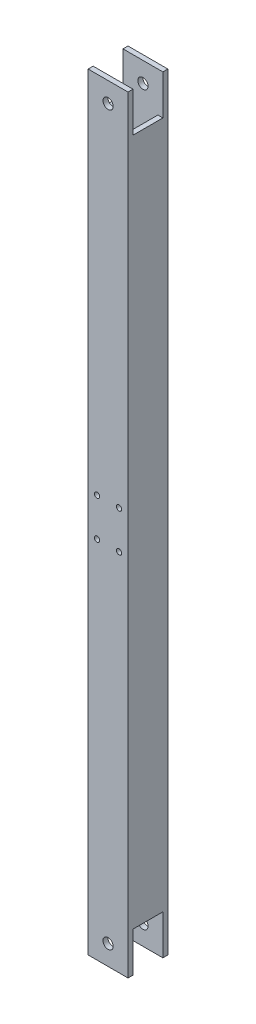
SolidWorks part; units mm, degrees
material "6061 Alloy"
ref_plane "Front Plane" through (0, 0, 0) normal (0, 0, 1) x (1, 0, 0)
ref_plane "Top Plane" through (0, 0, 0) normal (0, 1, 0) x (1, 0, 0)
ref_plane "Right Plane" through (0, 0, 0) normal (1, 0, 0) x (0, 0, -1)
sketch "Sketch1" plane through (0, 0, 0) normal (0, 1, 0) x (1, 0, 0)
  line L0 (3.175, -3.175) -> (22.225, -3.175)
  line L1 (0, 0) -> (25.4, 0)
  line L2 (0, 0) -> (0, -25.4)
  line L3 (0, -25.4) -> (25.4, -25.4)
  line L4 (25.4, 0) -> (25.4, -25.4)
  line L5 (22.225, -3.175) -> (22.225, -22.225)
  line L6 (3.175, -22.225) -> (22.225, -22.225)
  line L7 (3.175, -3.175) -> (3.175, -22.225)
  dimension "D1" = 25.4
  dimension "D2" = 25.4
  dimension "D3" = 3.175
extrude "Boss-Extrude1" add sketch "Sketch1" along normal blind 488.95
sketch "Sketch2" plane through (0, 0, 0) normal (0, 0, -1) x (-1, 0, 0)
  line L0 (-12.7, 488.95) -> (-12.7, 0)
  line L1 (-25.4, 488.95) -> (0, 488.95) construction
  line L2 (-25.4, 0) -> (0, 0) construction
  circle A0 centre (-12.7, 244.475) radius 14
  circle A1 centre (1.3, 244.475) radius 1.7
  circle A2 centre (-5.7, 232.3506) radius 1.7
  circle A3 centre (-19.7, 232.3506) radius 1.7
  circle A4 centre (-26.7, 244.475) radius 1.7
  circle A5 centre (-19.7, 256.5994) radius 1.7
  circle A6 centre (-5.7, 256.5994) radius 1.7
  point P23 (-12.7, 244.475)
  dimension "D1" = 28
  dimension "D2" = 3.4
  dimension "D3" = 6
extrude "Cut-Extrude1" cut sketch "Sketch2" against normal up to surface (25.4 mm away) contours A6 | A5 | A3 | A2 up to face at (12.7, 244.475, 25.4)
sketch "Sketch5" plane through (0, 0, 0) normal (-1, 0, 0) x (0, 0, 1)
  line L0 (3.175, 0) -> (22.225, 0)
  line L2 (3.175, 0) -> (3.175, 25.4006)
  line L3 (3.175, 25.4006) -> (22.225, 25.4006)
  line L4 (22.225, 25.4006) -> (22.225, 0)
  point P3 (12.7, 0)
extrude "Cut-Extrude2" cut sketch "Sketch5" against normal through all
ref_plane "Plane1" through (0, 244.475, 0) normal (0, 1, 0) x (1, 0, 0)
mirror "Mirror1" about plane through (0, 244.475, 0) normal (0, 1, 0) of "Cut-Extrude2"
sketch "Sketch6" plane through (0, 0, 25.4) normal (0, 0, 1) x (1, 0, 0)
  line L0 (0, 0) -> (25.4, 0)
  line L1 (55, 0) -> (-55, 0) construction
  line L2 (25.4, 488.95) -> (25.4, 0) construction
  line L3 (12.7, 0) -> (12.7, 12.7)
  circle A0 centre (12.7, 12.7) radius 3.2639
  dimension "D2" = 6.5278
  dimension "D1" = 12.7
extrude "Cut-Extrude3" cut sketch "Sketch6" against normal up to surface (25.4 mm away) up to face at (4, 232.3506, 0)
mirror "Mirror2" about plane through (0, 244.475, 0) normal (0, 1, 0) of "Cut-Extrude3"
